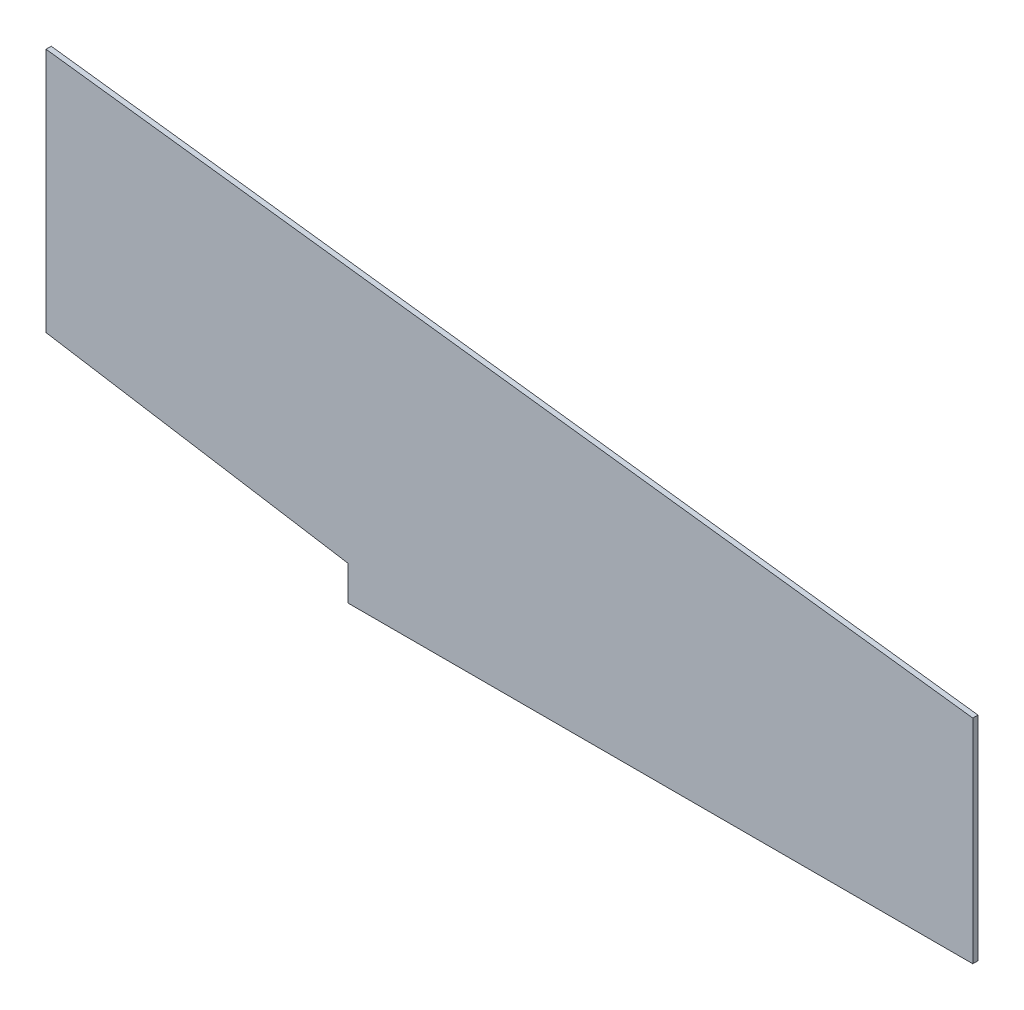
SolidWorks part; units mm, degrees
ref_plane "Front Plane" through (0, 0, 0) normal (0, 0, 1) x (1, 0, 0)
ref_plane "Top Plane" through (0, 0, 0) normal (0, 1, 0) x (1, 0, 0)
ref_plane "Right Plane" through (0, 0, 0) normal (1, 0, 0) x (0, 0, -1)
sketch "Sketch1" plane through (0, 0, 0) normal (0, 0, 1) x (1, 0, 0)
  line L0 (172.2857, 133.2344) -> (172.2857, 51.4916)
  line L1 (172.2857, 51.4916) -> (-67.7143, 51.4916)
  line L2 (-67.7143, 51.4916) -> (-67.7143, 64.7312)
  line L3 (-67.7143, 64.7312) -> (-183.7143, 83.4659)
  line L4 (-183.7143, 83.4659) -> (-183.7143, 177.7344)
  line L5 (-183.7143, 177.7344) -> (172.2857, 133.2344)
extrude "Boss-Extrude1" add sketch "Sketch1" along normal blind 2
